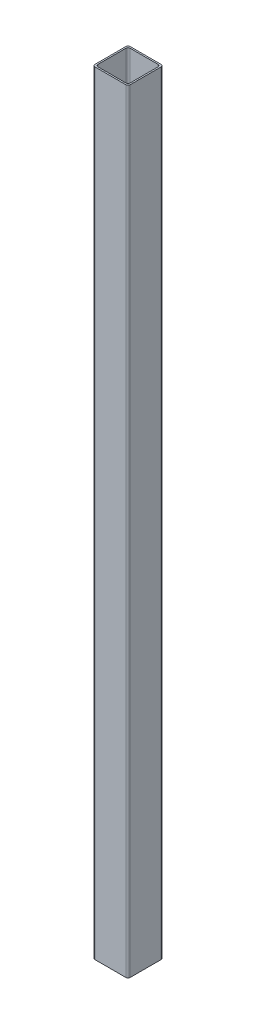
SolidWorks part; units mm, degrees
material "Brass"
ref_plane "Front Plane" through (0, 0, 0) normal (0, 0, 1) x (1, 0, 0)
ref_plane "Top Plane" through (0, 0, 0) normal (0, 1, 0) x (1, 0, 0)
ref_plane "Right Plane" through (0, 0, 0) normal (1, 0, 0) x (0, 0, -1)
sketch "Sketch1" plane through (0, 0, 0) normal (0, 1, 0) x (1, 0, 0)
  line L1 (-1.625, -1.875) -> (1.625, -1.875)
  line L2 (-1.875, -1.625) -> (-1.875, 1.625)
  line L3 (-1.625, 1.875) -> (1.625, 1.875)
  line L4 (1.875, -1.625) -> (1.875, 1.625)
  line L5 (-1.875, -1.875) -> (1.875, 1.875) construction
  line L6 (-1.875, 1.875) -> (1.875, -1.875) construction
  line L7 (-1.8, -2.05) -> (1.8, -2.05)
  line L8 (-2.05, -1.8) -> (-2.05, 1.8)
  line L9 (-1.8, 2.05) -> (1.8, 2.05)
  line L10 (2.05, -1.8) -> (2.05, 1.8)
  line L11 (-2.05, -2.05) -> (2.05, 2.05) construction
  line L12 (-2.05, 2.05) -> (2.05, -2.05) construction
  arc A0 (-1.8, -2.05) -> (-2.05, -1.8) centre (-1.8, -1.8) cw
  arc A1 (-2.05, 1.8) -> (-1.8, 2.05) centre (-1.8, 1.8) cw
  arc A2 (1.8, 2.05) -> (2.05, 1.8) centre (1.8, 1.8) cw
  arc A3 (1.8, -2.05) -> (2.05, -1.8) centre (1.8, -1.8) ccw
  arc A4 (1.625, -1.875) -> (1.875, -1.625) centre (1.625, -1.625) ccw
  arc A5 (1.625, 1.875) -> (1.875, 1.625) centre (1.625, 1.625) cw
  arc A6 (-1.875, 1.625) -> (-1.625, 1.875) centre (-1.625, 1.625) cw
  arc A7 (-1.625, -1.875) -> (-1.875, -1.625) centre (-1.625, -1.625) cw
  point P0 (0, 0)
  point P6 (0, 0)
  dimension "D3" = 0.25
  dimension "D1" = 4.1
  dimension "D2" = 3.75
extrude "Boss-Extrude1" add sketch "Sketch1" along normal blind 90
